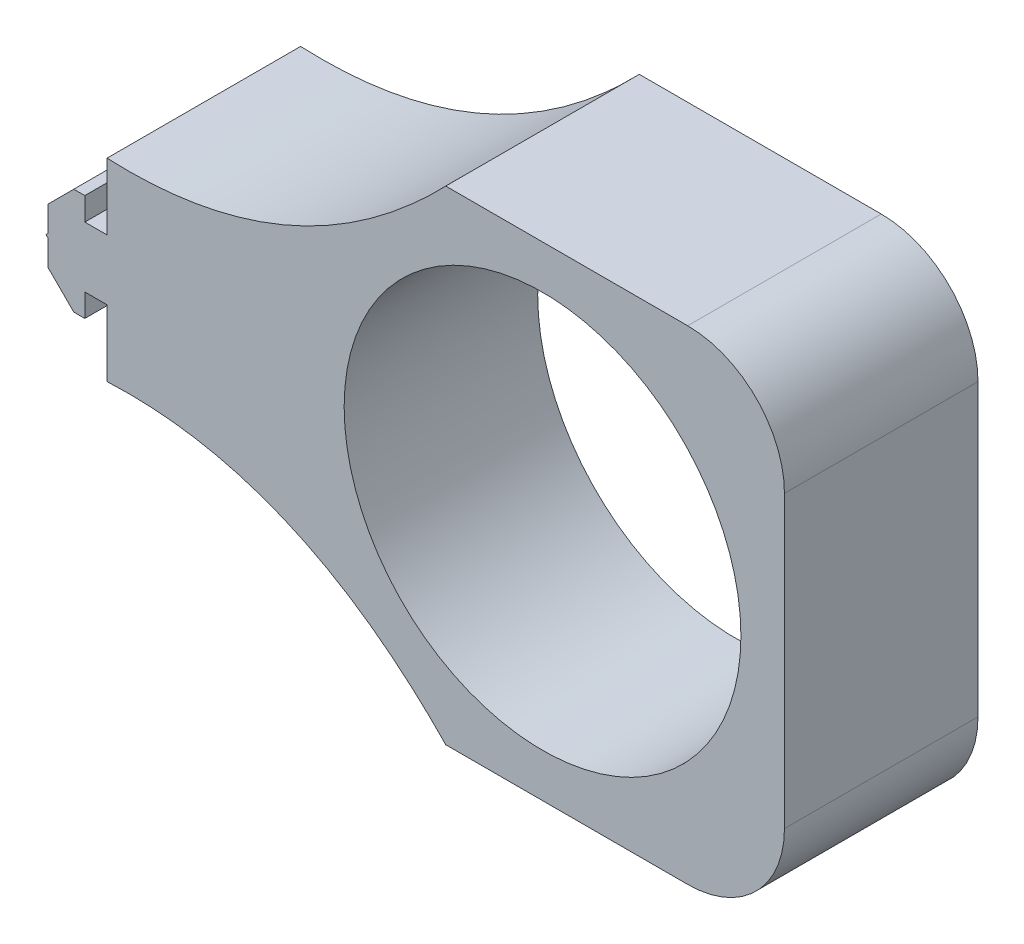
SolidWorks part; units mm, degrees
ref_plane "Front Plane" through (0, 0, 0) normal (0, 0, 1) x (1, 0, 0)
ref_plane "Top Plane" through (0, 0, 0) normal (0, 1, 0) x (1, 0, 0)
ref_plane "Right Plane" through (0, 0, 0) normal (1, 0, 0) x (0, 0, -1)
sketch "Sketch1" plane through (0, 0, 0) normal (0, 0, 1) x (1, 0, 0)
  line L1 (-25, -25) -> (25, -25)
  line L2 (-25, -25) -> (-25, 25)
  line L3 (-25, 25) -> (25, 25)
  line L4 (25, -25) -> (25, 25)
  line L5 (-25, -25) -> (25, 25) construction
  line L6 (-25, 25) -> (25, -25) construction
  circle A0 centre (0, 0) radius 20.5
  point P0 (0, 0)
  dimension "D3" = 41
  dimension "D1" = 50
  dimension "D2" = 50
extrude "Boss-Extrude1" add sketch "Sketch1" along normal blind 20
sketch "Sketch2" plane through (-25, 0, 0) normal (-1, 0, 0) x (0, 0, 1)
  line L1 (20, -25) -> (0, -25)
  line L2 (20, -25) -> (20, 25)
  line L3 (20, 25) -> (0, 25)
  line L4 (0, -25) -> (0, 25)
extrude "Boss-Extrude2" add sketch "Sketch2" along normal blind 20
sketch "Sketch3" plane through (0, 0, 20) normal (0, 0, 1) x (1, 0, 0)
  line L0 (-45, -10) -> (-45, 10)
  line L1 (-45, -25) -> (-45, 25) construction
  line L2 (25, 25) -> (-45, 25) construction
  line L3 (-1000, 0) -> (49000, 0) construction
  line L8 (25, -25) -> (25, 25)
  line L9 (25, 25) -> (-45, 25)
  line L10 (-45, 25) -> (-45, -25)
  line L11 (-45, -25) -> (25, -25)
  line L12 (25, -25) -> (25, 25)
  line L13 (25, 25) -> (-45, 25)
  line L14 (-45, 25) -> (-45, -25)
  line L15 (-45, -25) -> (25, -25)
  spline S0 degree 2 poles (-45, 10) (-25.3728, 9.0722) (-10, 25) knots 0 0 0 1 1 1
  spline S1 degree 2 poles (-45, -10) (-25.3728, -9.0722) (-10, -25) knots 0 0 0 1 1 1
  point P4 (-45, 0)
  line M9 (-45, 25) -> (-45, -25)
  line M10 (-45, -25) -> (25, -25)
  dimension "D2" = 0
  dimension "D1" = 20
extrude "Cut-Extrude1" cut sketch "Sketch3" against normal blind 20 contours S0 L13 M9 | S1 M9 M10
sketch "Sketch4" plane through (0, 0, 20) normal (0, 0, 1) x (1, 0, 0)
  line L0 (-45, -3.125) -> (-47.3, -3.125)
  line L5 (-45, 3.125) -> (-45, 5.5)
  line L7 (-45, 3.125) -> (-47.3, 3.125)
  line L8 (-47.3, 3.125) -> (-47.3, 5.5)
  line L9 (-45, 5.5) -> (-47.3, 5.5)
  line L10 (-47.3, -3.125) -> (-47.3, -5.5)
  line L12 (-45, -10) -> (-45, 10) construction
  point P10 (-45, 0)
  line B0 (-55, 0) -> (-45, 0) construction
  line B1 (-51.31, 0) -> (-51.1, 0.21)
  line B2 (-51.1, 0.21) -> (-51.1, 2.8393)
  line B3 (-51.1, 2.8393) -> (-48.4393, 5.5)
  line B4 (-48.4393, 5.5) -> (-46.8, 5.5)
  line B5 (-46.8, 5.5) -> (-46.8, 3.125)
  line B6 (-46.8, 3.125) -> (-46.455, 3.125)
  line B7 (-46.455, 3.125) -> (-45, 4.58)
  line B8 (-45, 4.58) -> (-45, -4.58)
  line B9 (-55, 0) -> (-49.0868, 5.9132) construction
  line B10 (-46.455, -3.125) -> (-45, -4.58)
  line B11 (-46.8, -3.125) -> (-46.455, -3.125)
  line B12 (-46.8, -5.5) -> (-46.8, -3.125)
  line B13 (-48.4393, -5.5) -> (-46.8, -5.5)
  line B14 (-51.1, -2.8393) -> (-48.4393, -5.5)
  line B15 (-51.1, -0.21) -> (-51.1, -2.8393)
  line B16 (-51.31, 0) -> (-51.1, -0.21)
sketch_block_instance "V Slot 1-5"
sketch_block "V Slot 1" parameters "D1"=10, "D2"=11, "D3"=4.3, "D4"=1.8, "D5"=0.21, "D6"=45, "D7"=9.16, "D8"=1.5, "D9"=6.25
extrude "Boss-Extrude3" add sketch "Sketch4" against normal blind 20
fillet "Fillet1" radius 10 2 edges at (25, 25, 10) (25, -25, 10)
